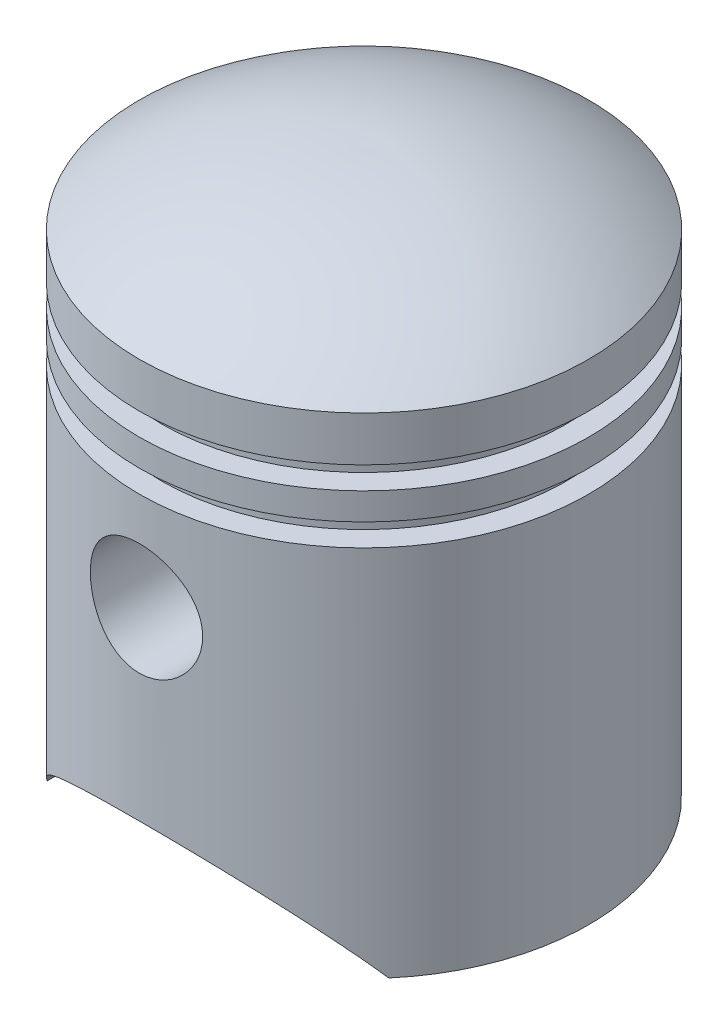
SolidWorks part; units mm, degrees
ref_plane "Front Plane" through (0, 0, 0) normal (0, 0, 1) x (1, 0, 0)
ref_plane "Top Plane" through (0, 0, 0) normal (0, 1, 0) x (1, 0, 0)
ref_plane "Right Plane" through (0, 0, 0) normal (1, 0, 0) x (0, 0, -1)
sketch "Sketch1" plane through (0, 0, 0) normal (0, 0, 1) x (1, 0, 0)
  line L0 (0, 62.5) -> (0, 60.4994)
  line L1 (23, 0) -> (25, 0)
  line L2 (25, 0) -> (25, 41.5)
  line L3 (25, 41.5) -> (22.5, 41.5)
  line L4 (22.5, 41.5) -> (22.5, 44)
  line L5 (22.5, 44) -> (25, 44)
  line L6 (25, 44) -> (25, 47)
  line L7 (25, 47) -> (22.5, 47)
  line L8 (22.5, 47) -> (22.5, 49.5)
  line L9 (22.5, 49.5) -> (25, 49.5)
  line L10 (25, 49.5) -> (25, 54.5)
  line L11 (0, 62.5) -> (0, 0) construction
  line L13 (23, 0) -> (23, 39.5)
  line L14 (23, 39.5) -> (20.5, 39.5)
  line L15 (20.5, 39.5) -> (20.5, 45.5)
  line L16 (20.5, 45.5) -> (20.5, 45.5)
  line L17 (20.5, 45.5) -> (20.5, 45.5)
  line L18 (20.5, 45.5) -> (20.5, 45.5)
  line L19 (20.5, 45.5) -> (20.5, 51.5)
  line L20 (20.5, 51.5) -> (23, 51.5)
  line L21 (23, 51.5) -> (23, 53.4845)
  line L22 (23, 2) -> (23, 39.5) construction
  line L23 (2, 2) -> (23, 2) construction
  line L24 (0, 0) -> (25, 0) construction
  line L25 (2, 60.4985) -> (2, 2) construction
  arc A0 (25, 54.5) -> (0, 62.5) centre (0.9839, 22.5121) ccw
  arc A1 (23, 53.4845) -> (0, 60.4994) centre (0.9839, 22.5121) ccw
  arc A2 (23, 53.4845) -> (2, 60.4985) centre (0.9839, 22.5121) ccw construction
  dimension "D8" = 40
  dimension "D3" = 41.5
  dimension "D4" = 2.5
  dimension "D5" = 2.5
  dimension "D6" = 3
  dimension "D7" = 5
  dimension "D9" = 2
revolve "Revolve1" add sketch "Sketch1" angle 360 about L0
sketch "Sketch2" plane through (0, 0, 0) normal (0, 0, 1) x (1, 0, 0)
  line L0 (-19, 0) -> (19, 0)
  line L1 (-25, 0) -> (25, 0) construction
  line L2 (0, 0) -> (0, 10) construction
  arc A0 (-19, 0) -> (19, 0) centre (0, -13.05) cw
  dimension "D1" = 10
  dimension "D2" = 38
extrude "Cut-Extrude1" cut sketch "Sketch2" against normal mid plane 70
sketch "Sketch3" plane through (0, 0, 0) normal (0, 0, 1) x (1, 0, 0)
  line L0 (0, 62.5) -> (0, 30.5) construction
  circle A0 centre (0, 30.5) radius 6.25
  point P3 (0, 0)
  dimension "D2" = 12.5
  dimension "D1" = 32
extrude "Cut-Extrude2" cut sketch "Sketch3" against normal mid plane 70
ref_plane "Plane1" through (0, 0, 12) normal (0, 0, 1) x (1, 0, 0)
sketch "Sketch5" plane through (0, 0, 12) normal (0, 0, 1) x (1, 0, 0)
  circle A0 centre (0, 30.5) radius 6.25 construction
  circle A1 centre (0, 30.5) radius 6.25
  circle A2 centre (0, 30.5) radius 7.25
  dimension "D1" = 14.5
extrude "Boss-Extrude1" add sketch "Sketch5" along normal up to next
mirror "Mirror2" about plane through (0, 0, 0) normal (0, 0, 1) of "Boss-Extrude1"
